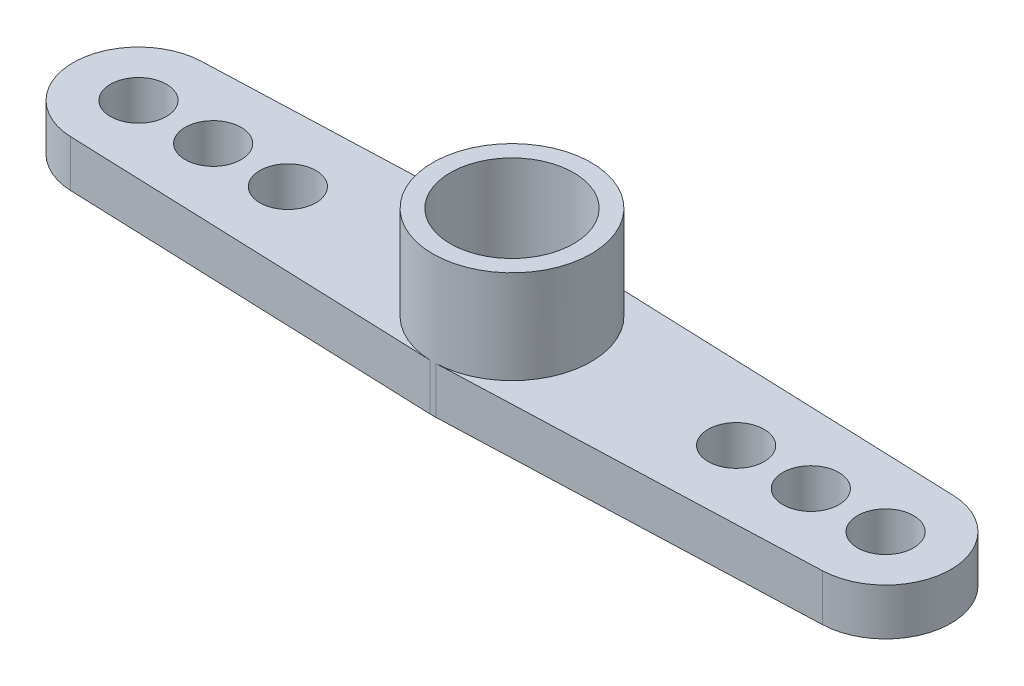
SolidWorks part; units mm, degrees
ref_plane "前视基准面" through (0, 0, 0) normal (0, 0, 1) x (1, 0, 0)
ref_plane "上视基准面" through (0, 0, 0) normal (0, 1, 0) x (1, 0, 0)
ref_plane "右视基准面" through (0, 0, 0) normal (1, 0, 0) x (0, 0, -1)
sketch "草图1" plane through (0, 0, 0) normal (0, 1, 0) x (1, 0, 0)
  line L0 (20.1293, -3.4976) -> (0.0783, -4.2388)
  line L5 (-20.1293, 3.4976) -> (-0.0783, 4.2388)
  line L11 (-20.1293, -3.4976) -> (-0.0783, -4.2388)
  line L12 (20.1293, 3.4976) -> (0.0783, 4.2388)
  circle A0 centre (0, 0) radius 3.3
  arc A1 (0.1566, 4.2359) -> (-0.1566, 4.2359) centre (0, 0) ccw
  circle A2 centre (-20, 0) radius 1.5
  circle A3 centre (-16, 0) radius 1.5
  circle A4 centre (-12, 0) radius 1.5
  arc A5 (-20.1293, 3.4976) -> (-20.1293, -3.4976) centre (-20, 0) ccw
  arc A6 (20.1293, -3.4976) -> (20.1293, 3.4976) centre (20, 0) ccw
  circle A7 centre (12, 0) radius 1.5
  circle A8 centre (16, 0) radius 1.5
  circle A9 centre (20, 0) radius 1.5
  arc A10 (-0.1566, -4.2359) -> (0.1566, -4.2359) centre (0, 0) ccw
  point P11 (0, 0)
  point P20 (0, 0)
  point P29 (0, 0)
  dimension "D1" = 2
  dimension "D2" = 2
extrude "凸台-拉伸2" add sketch "草图1" along normal blind 2.5 contours L11 A10 L0 A6 L12 A1 L5 A5 A0 A2 A3 A4 A7 A8 A9
sketch "草图2" plane through (0, 2.5, 0) normal (0, 1, 0) x (1, 0, 0)
  circle A0 centre (0, 0) radius 4.2388
  circle A1 centre (0, 0) radius 3.3
extrude "凸台-拉伸3" add sketch "草图2" along normal blind 5
sketch "草图3" plane through (0, 2.5, 0) normal (0, 1, 0) x (1, 0, 0)
  circle A0 centre (0, 0) radius 1.5
  circle A1 centre (0, 0) radius 3.7319
extrude "凸台-拉伸4" add sketch "草图3" against normal blind 2.5
